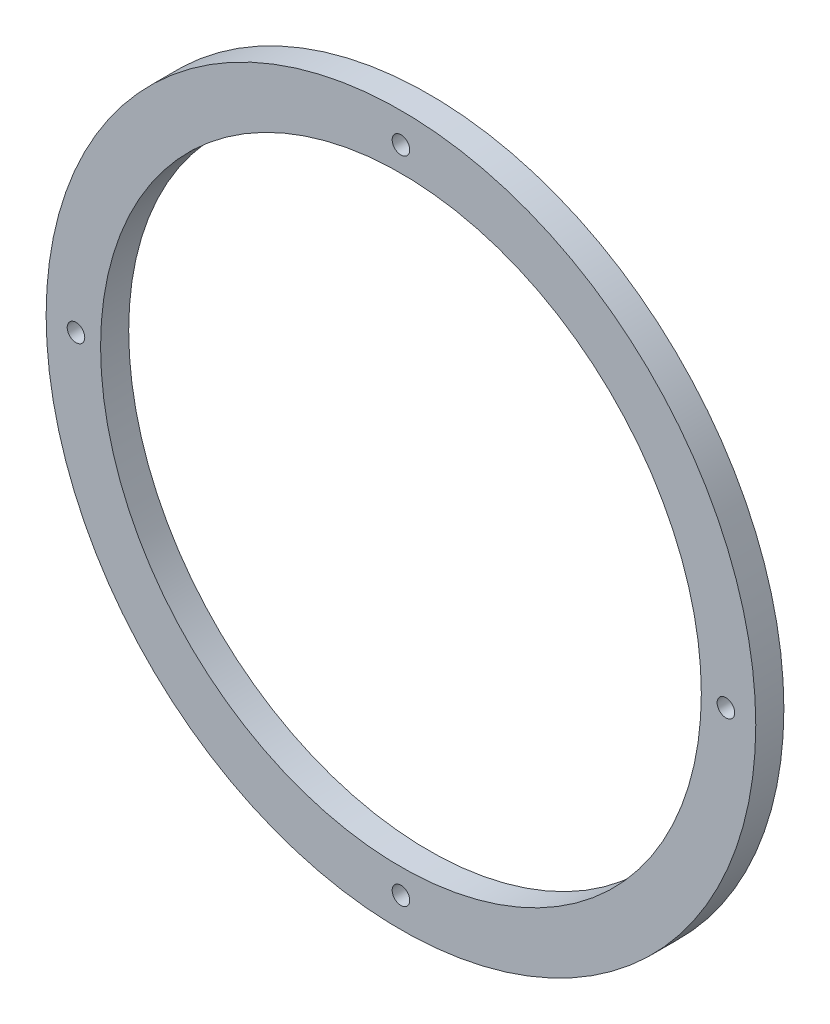
SolidWorks part; units mm, degrees
ref_plane "Front Plane" through (0, 0, 0) normal (0, 0, 1) x (1, 0, 0)
ref_plane "Top Plane" through (0, 0, 0) normal (0, 1, 0) x (1, 0, 0)
ref_plane "Right Plane" through (0, 0, 0) normal (1, 0, 0) x (0, 0, -1)
sketch "Sketch1" plane through (0, 0, 0) normal (0, 0, 1) x (1, 0, 0)
  circle A0 centre (0, 0) radius 101
  circle A1 centre (0, 0) radius 85.5
  dimension "D1" = 202
  dimension "D2" = 171
extrude "Boss-Extrude1" add sketch "Sketch1" along normal blind 8
sketch "Sketch2" plane through (0, 0, 8) normal (0, 0, 1) x (1, 0, 0)
  circle A0 centre (0, 92.5) radius 2.5
  circle A1 centre (92.5, 0) radius 2.5
  circle A2 centre (0, -92.5) radius 2.5
  circle A3 centre (-92.5, 0) radius 2.5
  point P2 (-121.7629, -29.518)
  point P4 (0, 0)
  point P12 (0, 0)
  dimension "D1" = 5
  dimension "D2" = 92.5
  dimension "D3" = 4
extrude "Cut-Extrude1" cut sketch "Sketch2" against normal through all
